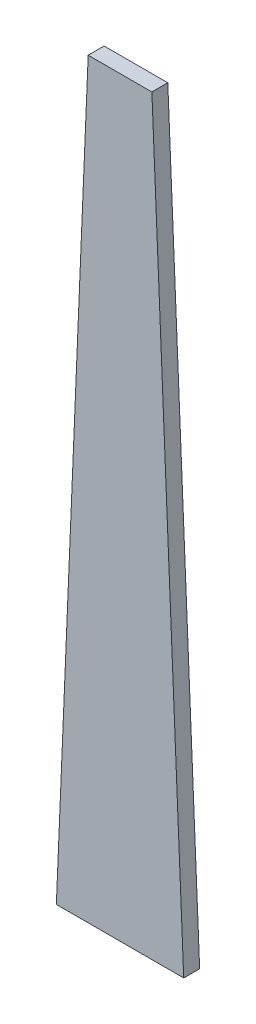
SolidWorks part; units mm, degrees
ref_plane "Front Plane" through (0, 0, 0) normal (0, 0, 1) x (1, 0, 0)
ref_plane "Top Plane" through (0, 0, 0) normal (0, 1, 0) x (1, 0, 0)
ref_plane "Right Plane" through (0, 0, 0) normal (1, 0, 0) x (0, 0, -1)
sketch "Sketch1" plane through (0, 0, 0) normal (0, 0, 1) x (1, 0, 0)
  line L0 (-25.4, 0) -> (25.4, 0)
  line L1 (25.4, 0) -> (12.7, 299.72)
  line L2 (12.7, 299.72) -> (-12.7, 299.72)
  line L3 (-12.7, 299.72) -> (-25.4, 0)
  line L4 (0, 0) -> (0, 299.72) construction
  point P7 (0, 0)
  point P8 (0, 0)
  point P9 (0, 299.72)
  point P10 (0, 0)
  point P11 (0, 0)
  point P12 (0, 0)
  dimension "D1" = 299.72
  dimension "D2" = 25.4
  dimension "D3" = 50.8
extrude "Boss-Extrude1" add sketch "Sketch1" along normal blind 6.35
